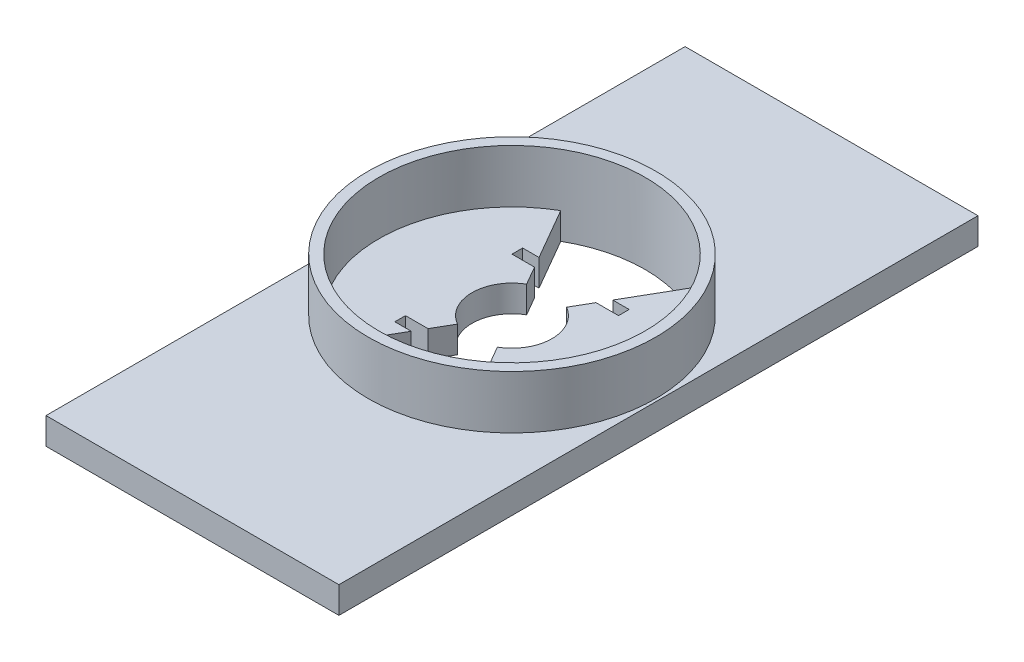
SolidWorks part; units mm, degrees
ref_plane "Front Plane" through (0, 0, 0) normal (0, 0, 1) x (1, 0, 0)
ref_plane "Top Plane" through (0, 0, 0) normal (0, 1, 0) x (1, 0, 0)
ref_plane "Right Plane" through (0, 0, 0) normal (1, 0, 0) x (0, 0, -1)
sketch "Sketch1" plane through (0, 0, 0) normal (0, 1, 0) x (1, 0, 0)
  line L1 (-51, 60) -> (51, 60)
  line L2 (-51, 60) -> (-51, -60)
  line L3 (-51, -60) -> (51, -60)
  line L4 (51, 60) -> (51, -60)
  line L5 (-51, 60) -> (51, -60) construction
  line L6 (-51, -60) -> (51, 60) construction
  line L7 (-10, -12) -> (10, -12)
  line L8 (-10, -12) -> (-10, -10)
  line L9 (-10, -10) -> (10, -10)
  line L10 (10, -12) -> (10, -10)
  line L11 (-10, 10) -> (10, 10)
  line L12 (-10, 10) -> (-10, 12)
  line L13 (-10, 12) -> (10, 12)
  line L14 (10, 10) -> (10, 12)
  point P0 (0, 0)
  dimension "D1" = 102
  dimension "D2" = 120
extrude "Boss-Extrude1" add sketch "Sketch1" along normal blind 5
sketch "Sketch2" plane through (0, 5, 0) normal (0, 1, 0) x (1, 0, 0)
  line L0 (0, 0) -> (4.0099, 0) construction
  line L1 (3.75, 6.4952) -> (12.5, 21.6506)
  line L2 (-3.75, 6.4952) -> (-12.5, 21.6506)
  line L3 (-3.75, -6.4952) -> (-12.5, -21.6506)
  line L4 (3.75, -6.4952) -> (12.5, -21.6506)
  arc A0 (12.5, 21.6506) -> (-12.5, 21.6506) centre (0, 0) ccw
  arc A2 (3.75, -6.4952) -> (3.75, 6.4952) centre (0, 0) ccw
  arc A3 (12.5, -21.6506) -> (-12.5, -21.6506) centre (0, 0) cw
  arc A4 (-3.75, 6.4952) -> (-3.75, -6.4952) centre (0, 0) ccw
  dimension "D1" = 120
  dimension "48" = 50
  dimension "D3" = 15
  dimension "D2" = 60
extrude "Cut-Extrude12" cut sketch "Sketch2" against normal blind 10 contours L4 A3 L3 A4 L2 A0 L1 A2
sketch "Sketch5" plane through (0, 5, 0) normal (0, 1, 0) x (1, 0, 0)
  circle A0 centre (0, 0) radius 25
  circle A1 centre (0, 0) radius 27
  dimension "D1" = 2
extrude "Boss-Extrude3" add sketch "Sketch5" along normal blind 10
sketch "Sketch6" plane through (0, 5, 0) normal (0, 1, 0) x (1, 0, 0)
  line L0 (51, 60) -> (-51, 60) construction
  line L1 (-51, -60) -> (-27.5, -60)
  line L2 (-51, -60) -> (-51, 60)
  line L3 (-51, 60) -> (-27.5, 60)
  line L4 (-27.5, -60) -> (-27.5, 60)
  line L6 (51, -60) -> (27.5, -60)
  line L7 (51, -60) -> (51, 60)
  line L8 (51, 60) -> (27.5, 60)
  line L9 (27.5, -60) -> (27.5, 60)
  dimension "D1" = 23.5
  dimension "D2" = 23.5
extrude "Cut-Extrude15" cut sketch "Sketch6" against normal blind 10 contours L2 L1 L4 L3 | L7 L6 L9 L8
